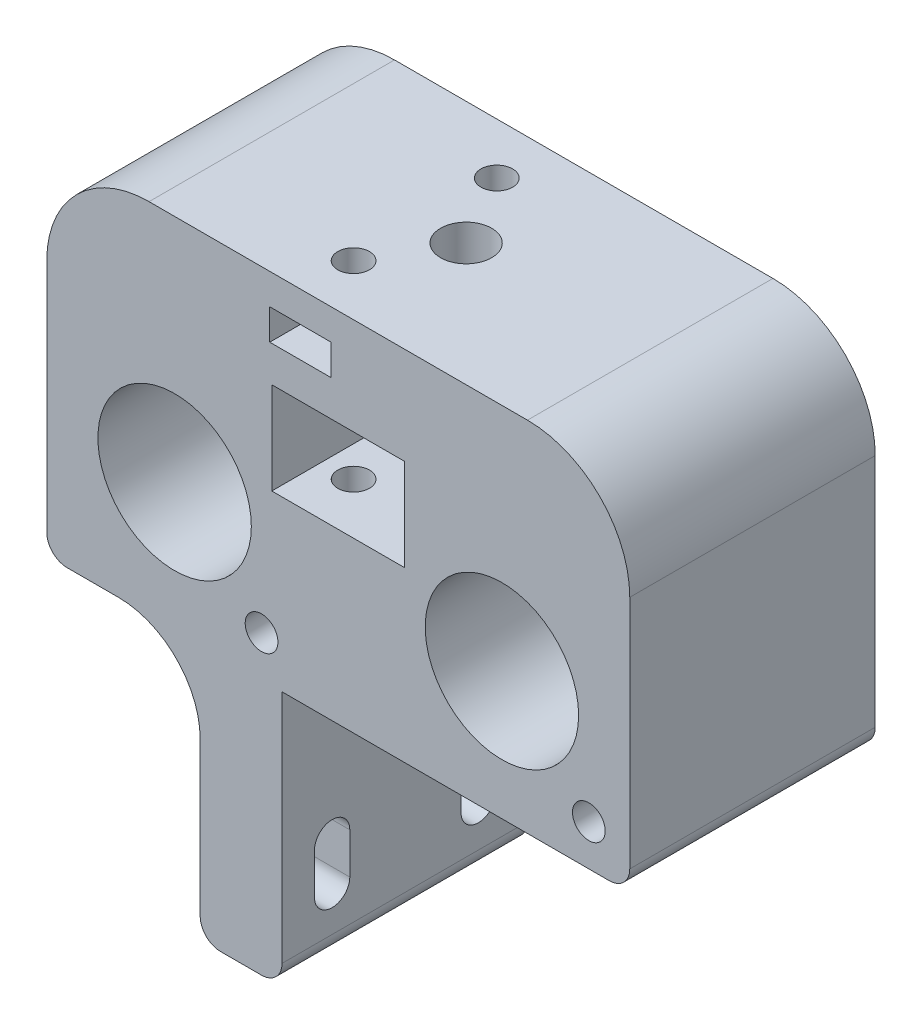
SolidWorks part; units mm, degrees
ref_plane "前视基准面" through (0, 0, 0) normal (0, 0, 1) x (1, 0, 0)
ref_plane "上视基准面" through (0, 0, 0) normal (0, 1, 0) x (1, 0, 0)
ref_plane "右视基准面" through (0, 0, 0) normal (1, 0, 0) x (0, 0, -1)
sketch "草图1" plane through (0, 0, 0) normal (0, 1, 0) x (1, 0, 0)
  line L1 (-24.2998, 11.8642) -> (32.7002, 11.8642)
  line L2 (-24.2998, 11.8642) -> (-24.2998, -12.1358)
  line L3 (-24.2998, -12.1358) -> (32.7002, -12.1358)
  line L4 (32.7002, 11.8642) -> (32.7002, -12.1358)
  dimension "D1" = 57
  dimension "D2" = 24
extrude "凸台-拉伸1" add sketch "草图1" along normal blind 25
sketch "草图2" plane through (0, 0, 12.1358) normal (0, 0, 1) x (1, 0, 0)
  line L0 (-24.2998, 12.5) -> (32.7002, 12.5) construction
  line L1 (-24.2998, 25) -> (-24.2998, 0) construction
  line L2 (32.7002, 25) -> (32.7002, 0) construction
  circle A0 centre (-11.7998, 12.5) radius 7.5
  circle A1 centre (20.2002, 12.5) radius 7.5
  dimension "D1" = 15
  dimension "D2" = 15
  dimension "D3" = 32
  dimension "D4" = 12.5
extrude "切除-拉伸1" cut sketch "草图2" against normal through all
sketch "草图3" plane through (0, 0, 0) normal (0, -1, 0) x (1, 0, 0)
  line L0 (-24.2998, 12.1358) -> (32.7002, 12.1358) construction
  line L1 (-9.2998, 12.1358) -> (-1.2998, 12.1358)
  line L2 (-9.2998, 12.1358) -> (-9.2998, -11.8642)
  line L3 (-9.2998, -11.8642) -> (-1.2998, -11.8642)
  line L4 (-1.2998, 12.1358) -> (-1.2998, -11.8642)
  line L5 (32.7002, -11.8642) -> (-24.2998, -11.8642) construction
  line L6 (-24.2998, -11.8642) -> (-24.2998, 12.1358) construction
  dimension "D1" = 8
  dimension "D2" = 15
extrude "凸台-拉伸2" add sketch "草图3" along normal blind 25
sketch "草图4" plane through (-9.2998, 0, 0) normal (-1, 0, 0) x (0, 0, 1)
  line L1 (-7.0642, -19) -> (-7.0642, -15) construction
  line L2 (-8.7584, -19) -> (-8.7584, -15)
  line L3 (-5.37, -19) -> (-5.37, -15)
  line L4 (7.2358, -19) -> (7.2358, -15) construction
  line L5 (5.5091, -19) -> (5.5091, -15)
  line L6 (8.9625, -19) -> (8.9625, -15)
  line L7 (12.1358, -25) -> (-11.8642, -25) construction
  arc A2 (-8.7584, -19) -> (-5.37, -19) centre (-7.0642, -19) ccw
  arc A3 (-5.37, -15) -> (-8.7584, -15) centre (-7.0642, -15) ccw
  arc A4 (5.5091, -19) -> (8.9625, -19) centre (7.2358, -19) ccw
  arc A5 (8.9625, -15) -> (5.5091, -15) centre (7.2358, -15) ccw
  point P5 (-7.0642, -17)
  point P12 (7.2358, -17)
  dimension "D1" = 6
  dimension "D2" = 6
  dimension "D5" = 3.3883
  dimension "D6" = 4
  dimension "D7" = 3.4534
  dimension "D8" = 4
extrude "切除-拉伸2" cut sketch "草图4" against normal through all and the other way through all
sketch "草图5" plane through (0, 0, 0) normal (0, -1, 0) x (1, 0, 0)
  circle A2 centre (4.7002, 0.1355) radius 2.5
  dimension "D1" = 5
extrude "切除-拉伸3" cut sketch "草图5" against normal through all
fillet "圆角1" radius 8 1 edges at (-9.2998, 0, 0.1358)
sketch "草图6" plane through (0, 25, 0) normal (0, 1, 0) x (1, 0, 0)
  line L4 (-24.2998, 11.8642) -> (-24.2998, -12.1358)
  line L5 (-24.2998, -12.1358) -> (32.7002, -12.1358)
  line L6 (32.7002, -12.1358) -> (32.7002, 11.8642)
  line L7 (32.7002, 11.8642) -> (-24.2998, 11.8642)
  line L8 (-24.2998, 11.8642) -> (-24.2998, -12.1358)
  line L9 (-24.2998, -12.1358) -> (32.7002, -12.1358)
  line L10 (32.7002, -12.1358) -> (32.7002, 11.8642)
  line L11 (32.7002, 11.8642) -> (-24.2998, 11.8642)
  circle A0 centre (4.7002, -0.1355) radius 2.5 construction
  circle A1 centre (4.7002, -0.1355) radius 2.5
  dimension "D1" = 0
extrude "凸台-拉伸3" add sketch "草图6" along normal blind 10
sketch "草图7" plane through (0, 0, 12.1358) normal (0, 0, 1) x (1, 0, 0)
  line L0 (-24.2998, 35) -> (32.7002, 35) construction
  line L1 (-2.2998, 25.5) -> (2.7002, 25.5)
  line L2 (-2.2998, 25.5) -> (-2.2998, 16.5)
  line L3 (-2.2998, 16.5) -> (2.7002, 16.5)
  line L5 (5.7002, 25.5) -> (10.7002, 25.5)
  line L7 (5.7002, 16.5) -> (10.7002, 16.5)
  line L8 (10.7002, 25.5) -> (10.7002, 16.5)
  line L9 (32.7002, 35) -> (32.7002, 0) construction
  line L10 (-24.2998, 35) -> (-24.2998, 0) construction
  line L12 (2.7002, 25.5) -> (5.7002, 25.5)
  line L13 (2.7002, 16.5) -> (5.7002, 16.5)
  dimension "D2" = 9
  dimension "D3" = 5
  dimension "D4" = 5
  dimension "D5" = 9.5
  dimension "D6" = 9.5
  dimension "D7" = 22
  dimension "D8" = 22
extrude "切除-拉伸4" cut sketch "草图7" against normal through all
sketch "草图8" plane through (0, 35, 0) normal (0, 1, 0) x (1, 0, 0)
  line L0 (-24.2998, -12.1358) -> (32.7002, -12.1358) construction
  line L1 (32.7002, 11.8642) -> (-24.2998, 11.8642) construction
  line L3 (-24.2998, 11.8642) -> (-24.2998, -12.1358) construction
  circle A0 centre (0.7002, -7.1358) radius 1.55
  circle A1 centre (0.7002, 6.8642) radius 1.55
  dimension "D1" = 3.1
  dimension "D2" = 3.1
  dimension "D3" = 5
  dimension "D4" = 5
  dimension "D5" = 25
  dimension "D6" = 25
extrude "切除-拉伸5" cut sketch "草图8" against normal through all
sketch "草图9" plane through (0, 0, 12.1358) normal (0, 0, 1) x (1, 0, 0)
  line L0 (-24.2998, 35) -> (32.7002, 35) construction
  line L1 (-2.4998, 32) -> (3.5002, 32)
  line L2 (-2.4998, 32) -> (-2.4998, 29)
  line L3 (-2.4998, 29) -> (3.5002, 29)
  line L4 (3.5002, 32) -> (3.5002, 29)
  line L5 (2.2502, 25.5) -> (2.2502, 35) construction
  dimension "D1" = 6
  dimension "D2" = 3
  dimension "D3" = 1.25
  dimension "D4" = 3
extrude "切除-拉伸6" cut sketch "草图9" against normal blind 8
sketch "草图10" plane through (0, 0, -11.8642) normal (0, 0, -1) x (-1, 0, 0)
  line L5 (-3.5002, 32) -> (2.4998, 32)
  line L6 (-3.5002, 32) -> (-3.5002, 29)
  line L7 (-3.5002, 29) -> (2.4998, 29)
  line L8 (2.4998, 32) -> (2.4998, 29)
extrude "切除-拉伸7" cut sketch "草图10" against normal blind 8
sketch "草图11" plane through (0, 0, -11.8642) normal (0, 0, -1) x (-1, 0, 0)
  line L0 (-32.7002, 0) -> (1.2998, 0) construction
  line L1 (-32.7002, 35) -> (-32.7002, 0) construction
  circle A0 centre (-28.7002, 4) radius 1.6
  circle A1 centre (3.2998, 4) radius 1.6
  dimension "D1" = 3.2
  dimension "D2" = 32
  dimension "D3" = 4
  dimension "D4" = 4
  dimension "D5" = 4
extrude "切除-拉伸8" cut sketch "草图11" against normal through all
fillet "圆角2" radius 10 2 edges at (-24.2998, 35, 0.1358) (32.7002, 35, 0.1358)
fillet "圆角3" radius 2 2 edges at (32.7002, 0, 0.1358) (-24.2998, 0, 0.1358)
fillet "圆角4" radius 2 2 edges at (-1.2998, -25, 0.1358) (-9.2998, -25, 0.1358)
